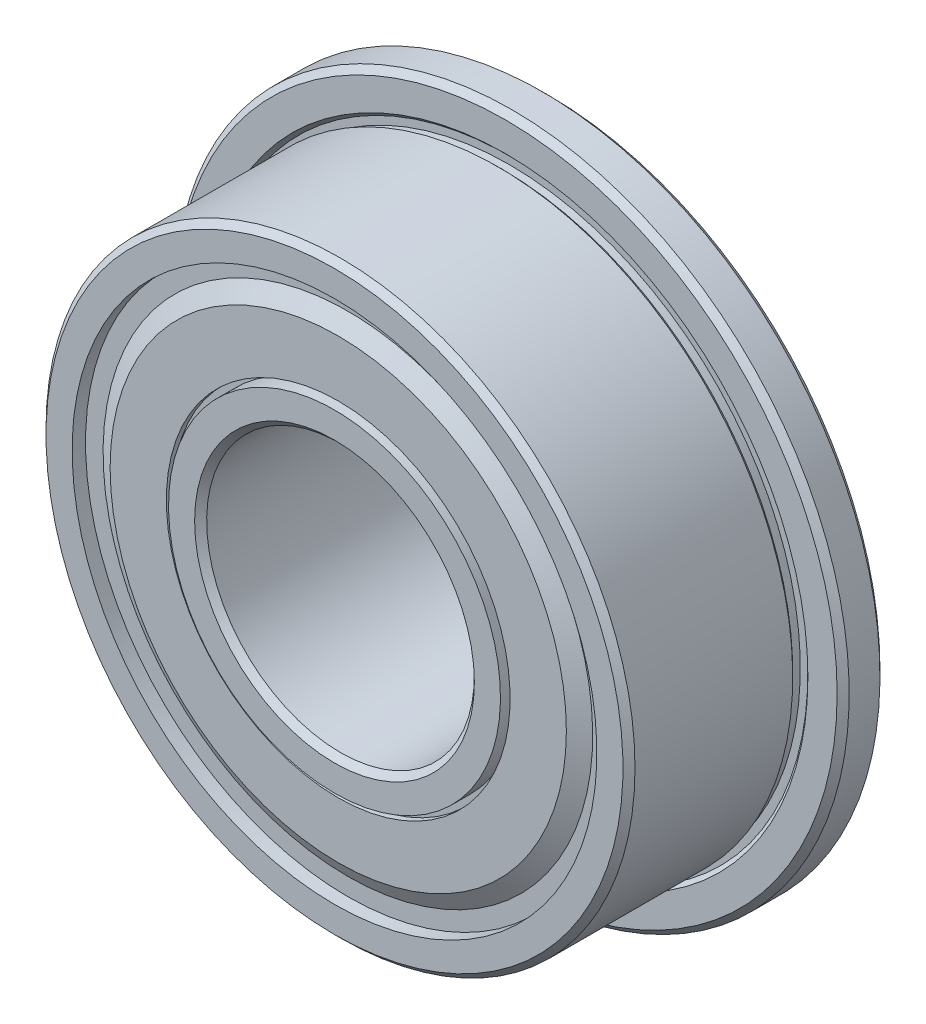
SolidWorks part; units mm, degrees
ref_plane "Front Plane" through (0, 0, 0) normal (0, 0, 1) x (1, 0, 0)
ref_plane "Top Plane" through (0, 0, 0) normal (0, 1, 0) x (1, 0, 0)
ref_plane "Right Plane" through (0, 0, 0) normal (1, 0, 0) x (0, 0, -1)
sketch "Sketch1" plane through (0, 0, 0) normal (1, 0, 0) x (0, 0, -1)
  line L0 (0, 5.5) -> (0, -5.5) construction
  line L1 (-2, 5.5) -> (2, 5.5) construction
  line L2 (0, 0) -> (2, 0) construction
  line L3 (2, 6.3) -> (2, -6.3) construction
  line L4 (2, -6.3) -> (1.2, -6.3) construction
  line L5 (2, 2.5) -> (0, 2.5) construction
  line L6 (2, 2.5) -> (2, -2.5) construction
  dimension "OD" = 11
  dimension "Width" = 4
  dimension "Flange Dia." = 12.6
  dimension "Flange Thickness" = 0.8
  dimension "ID" = 5
sketch "Sketch2" plane through (0, 0, 0) normal (1, 0, 0) x (0, 0, -1)
  line L0 (2, 6.3) -> (1.2, 6.3)
  line L1 (1.2, 6.3) -> (1.2, 5.6414)
  line L2 (1.0586, 5.5) -> (-2, 5.5)
  line L3 (-2, 5.5) -> (-2, 4.6)
  line L4 (-2, 4.6) -> (-0.45, 4.6)
  line L5 (2, 6.3) -> (2, -6.3) construction
  line L6 (2, 4.6) -> (2, 6.3)
  line L7 (2, 2.5) -> (-2, 2.5)
  line L8 (-2, 2.5) -> (-2, 3.4)
  line L9 (-2, 3.4) -> (-0.45, 3.4)
  line L10 (2, 3.4) -> (2, 2.5)
  line L11 (0, 5.5) -> (0, 2.5) construction
  line L12 (-0.75, 4) -> (0.75, 4) construction
  line L13 (0.45, 4.6) -> (2, 4.6)
  line L14 (0.45, 3.4) -> (2, 3.4)
  line L15 (1.2, 5.6414) -> (1.2707, 5.5707)
  line L16 (1.2707, 5.5707) -> (1.2707, 5.4293)
  line L17 (1.2707, 5.4293) -> (1.1293, 5.4293)
  line L18 (1.1293, 5.4293) -> (1.0586, 5.5)
  line L19 (1.2, 5.5) -> (1.2707, 5.4293) construction
  line L20 (1.2707, 5.5707) -> (1.1293, 5.4293) construction
  line L21 (1.0586, 5.5) -> (1.2, 5.5) construction
  line L22 (1.2, 5.5) -> (1.2, 5.6414) construction
  circle A0 centre (0, 4) radius 0.75 construction
  arc A1 (-0.45, 4.6) -> (0.45, 4.6) centre (0, 4) cw
  arc A2 (-0.45, 3.4) -> (0.45, 3.4) centre (0, 4) ccw
  dimension "D1" = 3
  dimension "Ball Dia." = 1.5
  dimension "D2" = 135
  dimension "D3" = 0.2
  dimension "D4" = 1.2
  dimension "Race Thikness" = 0.9
revolve "Revolve1" add sketch "Sketch2" angle 360 about L2
fillet "Fillet1" radius 0.1125 3 edges at (0, -6.3, -2) (0, -6.3, -1.2) (0, -5.5, 2) profile chamfer
sketch "Sketch3" plane through (0, 0, 0) normal (0, 0, 1) x (1, 0, 0)
  line L0 (-2.5, 0) -> (2.5, 0) construction
  line L1 (-5.5, 0) -> (5.5, 0) construction
  point P5 (0, 0)
  dimension "ID2" = 5
  dimension "OD2" = 11
fillet "Fillet2" radius 0.1125 2 edges at (0, -2.5, -2) (0, -2.5, 2) profile chamfer
sketch "Sketch7" plane through (0, 0, 0) normal (0, 0, 1) x (1, 0, 0)
  line L0 (0, 4.75) -> (0, 3.25)
  line L1 (0, 6.3) -> (0, -6.3) construction
  line L2 (-0.9067, 4.75) -> (0, 0) construction
  line L3 (0, 0) -> (0.9067, 4.75) construction
  line L4 (0.9067, 4.75) -> (-0.9067, 4.75) construction
  circle A0 centre (0, 4) radius 0.75 construction
  circle A1 centre (0, 0) radius 4.75 construction
  circle A2 centre (0, 0) radius 3.25 construction
  arc A4 (0, 4.75) -> (0, 3.25) centre (0, 4) ccw
  dimension "D1" = 21.614
revolve "Revolve3" add sketch "Sketch7" angle 360 about L0
pattern_circular "CirPattern3" count 13 over 360 about axis through (0, 0, 0) along (0, 0, 1) of bodies 107
sketch "Sketch8" plane through (0, 0, 0) normal (1, 0, 0) x (0, 0, -1)
  line L1 (-2, 4.6) -> (-1.64, 4.6)
  line L2 (-2, 4.6) -> (-2, 4.9)
  line L3 (-2, 4.9) -> (-1.64, 4.9)
  line L4 (-1.64, 4.6) -> (-1.64, 4.9)
  line L5 (2, 4.6) -> (1.64, 4.6)
  line L6 (2, 4.6) -> (2, 4.9)
  line L7 (2, 4.9) -> (1.64, 4.9)
  line L8 (1.64, 4.6) -> (1.64, 4.9)
  line L9 (2, 3.4) -> (1.64, 3.4)
  line L10 (2, 3.4) -> (2, 3.1)
  line L11 (2, 3.1) -> (1.64, 3.1)
  line L12 (1.64, 3.4) -> (1.64, 3.1)
  line L13 (-2, 3.4) -> (-1.64, 3.4)
  line L14 (-2, 3.4) -> (-2, 3.1)
  line L15 (-2, 3.1) -> (-1.64, 3.1)
  line L16 (-1.64, 3.4) -> (-1.64, 3.1)
  dimension "D1" = 0.3
  dimension "D2" = 0.36
revolve "Cut-Revolve1" cut sketch "Sketch8" angle 360 about L2
sketch "Sketch9" plane through (0, 0, 0) normal (1, 0, 0) x (0, 0, -1)
  line L0 (-1.64, 4.9) -> (-1.64, 4.5429)
  line L1 (-1.64, 4.5429) -> (-1.82, 4.2311)
  line L2 (-1.82, 4.2311) -> (-1.82, 3.21)
  line L3 (1.82, 3.21) -> (1.82, 3.1) construction
  line L4 (1.64, 4.9) -> (1.64, 4.5429)
  line L5 (1.64, 4.5429) -> (1.82, 4.2311)
  line L6 (1.82, 4.2311) -> (1.82, 3.21)
  line L7 (2, 3.1) -> (1.64, 3.1) construction
  line L8 (-1.75, 4.9) -> (-1.75, 4.5723)
  line L9 (-1.75, 4.5723) -> (-1.93, 4.2606)
  line L10 (-1.93, 4.2606) -> (-1.93, 3.21)
  line L11 (-1.64, 4.9) -> (-1.75, 4.9)
  line L12 (-1.82, 3.21) -> (-1.93, 3.21)
  line L13 (1.73, 4.9) -> (1.73, 4.567)
  line L14 (1.73, 4.567) -> (1.91, 4.2552)
  line L15 (1.91, 4.2552) -> (1.91, 3.21)
  line L16 (1.64, 4.9) -> (1.73, 4.9)
  line L17 (1.82, 3.21) -> (1.91, 3.21)
  line L18 (-1.64, 4.5429) -> (-1.64, 2.6) construction
  line L19 (1.64, 4.5429) -> (1.64, 4.9) construction
  line L20 (-1.64, 3.1) -> (-2, 3.1) construction
  line L22 (-1.82, 3.21) -> (-1.82, 3.1) construction
  point P13 (-1.75, 4.9)
  point P14 (0, 0)
  dimension "D2" = 150
  dimension "D1" = 150
  dimension "D5" = 0.36
  dimension "D3" = 0.11
  dimension "D4" = 0.09
  dimension "D6" = 0.3571
revolve "Revolve4" add sketch "Sketch9" angle 360 about L2
equation "\"Ball Dia.@Sketch2\"=\"D1@Sketch2\"*.5"
equation "\"D3@Sketch2\"=\"Flange Thickness@Sketch1\"/4"
equation "\"D1@Fillet1\"=\"Race Thikness@Sketch2\"/8"
equation "\"ID2@Sketch3\" = \"ID@Sketch1\""
equation "\"OD2@Sketch3\" = \"OD@Sketch1\""
equation "\"D1@Fillet2\"=\"Race Thikness@Sketch2\"/8"
equation "\"D1@CirPattern3\"=360/\"D1@Sketch7\"-4"
equation "\"D1@Sketch8\"=\"Race Thikness@Sketch2\"/3"
equation "\"D2@Sketch8\"=\"Race Thikness@Sketch2\"/2.5"
equation "\"D4@Sketch9\"=\"D5@Sketch9\"/4"
equation "\"D1@Sketch9\"=\"D2@Sketch9\""
equation "\"D4@Sketch2\"=\"D1@Sketch2\"*.4"
